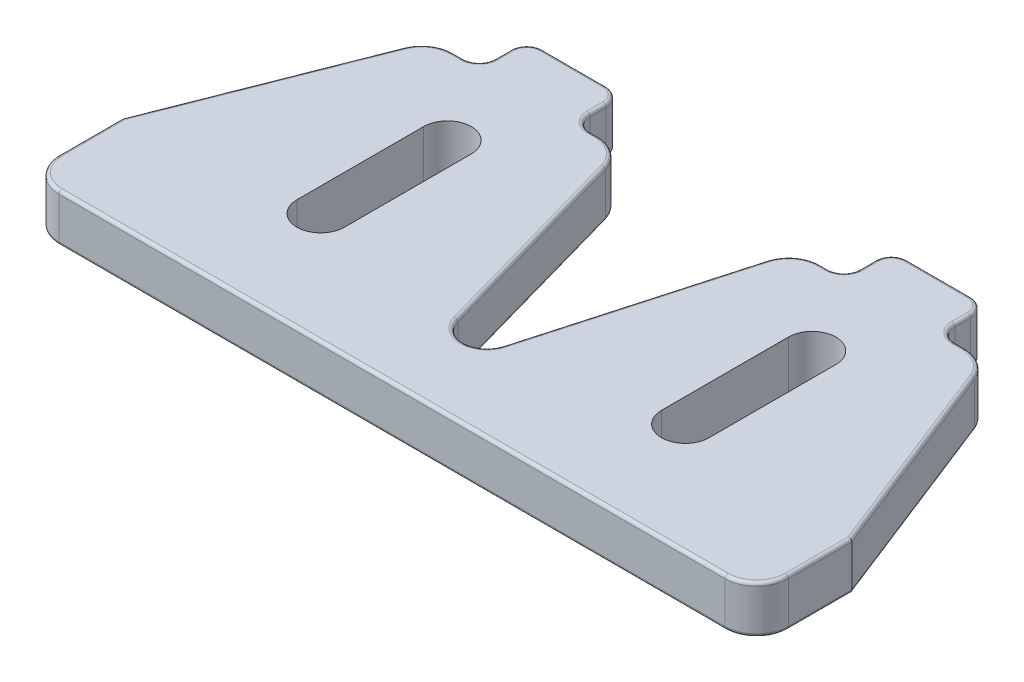
SolidWorks part; units mm, degrees
ref_plane "Front Plane" through (0, 0, 0) normal (0, 0, 1) x (1, 0, 0)
ref_plane "Top Plane" through (0, 0, 0) normal (0, 1, 0) x (1, 0, 0)
ref_plane "Right Plane" through (0, 0, 0) normal (1, 0, 0) x (0, 0, -1)
sketch "Sketch1" plane through (0, 0, 0) normal (0, 1, 0) x (1, 0, 0)
  line L0 (0, 0) -> (0, 17.8787) construction
  line L1 (21, 0) -> (-21, 0)
  line L2 (-23, 2) -> (-23, 6)
  line L3 (-23, 6) -> (-17.9984, 18.7313)
  line L4 (-16.1369, 20) -> (-15.5, 20)
  line L5 (-14.5, 21) -> (-14.5, 22)
  line L6 (-13.5, 23) -> (-9.5, 23)
  line L7 (-8.5, 22) -> (-8.5, 21)
  line L8 (-7.5, 20) -> (-7.0147, 20)
  line L9 (5.0895, 18.542) -> (1.4439, 5.5935)
  line L10 (-5.0895, 18.542) -> (-1.4439, 5.5935)
  line L11 (7.5, 20) -> (7.0147, 20)
  line L12 (8.5, 22) -> (8.5, 21)
  line L13 (13.5, 23) -> (9.5, 23)
  line L14 (14.5, 21) -> (14.5, 22)
  line L15 (16.1369, 20) -> (15.5, 20)
  line L16 (23, 6) -> (17.9984, 18.7313)
  line L17 (23, 2) -> (23, 6)
  line L18 (-11.5, 7) -> (-11.5, 15) construction
  line L19 (-13, 7) -> (-13, 15)
  line L20 (-10, 7) -> (-10, 15)
  line L21 (11.5, 7) -> (11.5, 15) construction
  line L22 (13, 7) -> (13, 15)
  line L23 (10, 7) -> (10, 15)
  arc A0 (-8.5, 21) -> (-7.5, 20) centre (-7.5, 21) ccw
  arc A1 (-1.4439, 5.5935) -> (1.4439, 5.5935) centre (0, 6) ccw
  arc A2 (-15.5, 20) -> (-14.5, 21) centre (-15.5, 21) ccw
  arc A3 (-5.0895, 18.542) -> (-7.0147, 20) centre (-7.0147, 18) ccw
  arc A4 (-17.9984, 18.7313) -> (-16.1369, 20) centre (-16.1369, 18) cw
  arc A5 (-9.5, 23) -> (-8.5, 22) centre (-9.5, 22) cw
  arc A6 (-14.5, 22) -> (-13.5, 23) centre (-13.5, 22) cw
  arc A7 (-21, 0) -> (-23, 2) centre (-21, 2) cw
  arc A8 (21, 0) -> (23, 2) centre (21, 2) ccw
  arc A9 (14.5, 22) -> (13.5, 23) centre (13.5, 22) ccw
  arc A10 (9.5, 23) -> (8.5, 22) centre (9.5, 22) ccw
  arc A11 (17.9984, 18.7313) -> (16.1369, 20) centre (16.1369, 18) ccw
  arc A12 (5.0895, 18.542) -> (7.0147, 20) centre (7.0147, 18) cw
  arc A13 (15.5, 20) -> (14.5, 21) centre (15.5, 21) cw
  arc A14 (8.5, 21) -> (7.5, 20) centre (7.5, 21) cw
  arc A15 (-13, 7) -> (-10, 7) centre (-11.5, 7) ccw
  arc A16 (-10, 15) -> (-13, 15) centre (-11.5, 15) ccw
  arc A17 (13, 7) -> (10, 7) centre (11.5, 7) cw
  arc A18 (10, 15) -> (13, 15) centre (11.5, 15) cw
  point P14 (-8.5, 20)
  point P19 (-14.5, 20)
  point P22 (-5.5, 20)
  point P25 (-17.5, 20)
  point P28 (-8.5, 23)
  point P31 (-14.5, 23)
  point P34 (-23, 0)
  point P57 (23, 0)
  point P58 (14.5, 23)
  point P59 (8.5, 23)
  point P60 (17.5, 20)
  point P61 (5.5, 20)
  point P62 (14.5, 20)
  point P63 (8.5, 20)
  point P66 (-11.5, 11)
  point P73 (11.5, 11)
  dimension "D8" = 6
  dimension "D9" = 1.5
  dimension "D11" = 1
  dimension "D12" = 2
  dimension "D13" = 1
  dimension "D14" = 2
  dimension "D1" = 6
  dimension "D2" = 23
  dimension "D3" = 3
  dimension "D4" = 3
  dimension "D5" = 5.5
  dimension "D6" = 20
  dimension "D7" = 6
  dimension "D10" = 3
  dimension "D15" = 3
  dimension "D16" = 8
  dimension "D17" = 7
  dimension "D18" = 10
extrude "Boss-Extrude1" add sketch "Sketch1" along normal blind 3
ref_plane "Plane1" through (0, 0, -15) normal (0, 0, 1) x (0, -1, 0)
fillet "Fillet1" radius 0.2 64 edges at (20.4992, 0, -12.3657) (17.2633, 0, -19.6527) (15.8185, 0, -20) (14.7929, 0, -20.2929) (14.5, 0, -21.5) (14.2071, 0, -22.7071) (11.5, 0, -23) (8.7929, 0, -22.7071) (8.5, 0, -21.5) (8.2071, 0, -20.2929) (7.2573, 0, -20) (5.8072, 0, -19.5944) (3.2667, 0, -12.0678) (0, 0, -4.5) (-20.4992, 0, -12.3657) (-17.2633, 0, -19.6527) (-15.8185, 0, -20) (-14.7929, 0, -20.2929) (-14.5, 0, -21.5) (-14.2071, 0, -22.7071) (-11.5, 0, -23) (-8.7929, 0, -22.7071) (-8.5, 0, -21.5) (-8.2071, 0, -20.2929) (-7.2573, 0, -20) (-5.8072, 0, -19.5944) (-20.4992, 3, -12.3657) (-17.2633, 3, -19.6527) (-15.8185, 3, -20) (-14.7929, 3, -20.2929) (-14.5, 3, -21.5) (-14.2071, 3, -22.7071) (-11.5, 3, -23) (-8.7929, 3, -22.7071) (-8.5, 3, -21.5) (-8.2071, 3, -20.2929) (-7.2573, 3, -20) (-5.8072, 3, -19.5944) (-3.2667, 3, -12.0678) (0, 3, -4.5) (3.2667, 3, -12.0678) (5.8072, 3, -19.5944) (7.2573, 3, -20) (8.2071, 3, -20.2929) (8.5, 3, -21.5) (8.7929, 3, -22.7071) (11.5, 3, -23) (14.2071, 3, -22.7071) (14.5, 3, -21.5) (14.7929, 3, -20.2929) (15.8185, 3, -20) (17.2633, 3, -19.6527) (-23, 0, -4) (-22.4142, 0, -0.5858) (23, 0, -4) (22.4142, 0, -0.5858) (-23, 3, -4) (-22.4142, 3, -0.5858) (23, 3, -4) (22.4142, 3, -0.5858) (-3.2667, 0, -12.0678) (20.4992, 3, -12.3657) (0, 0, 0) (0, 3, 0)
